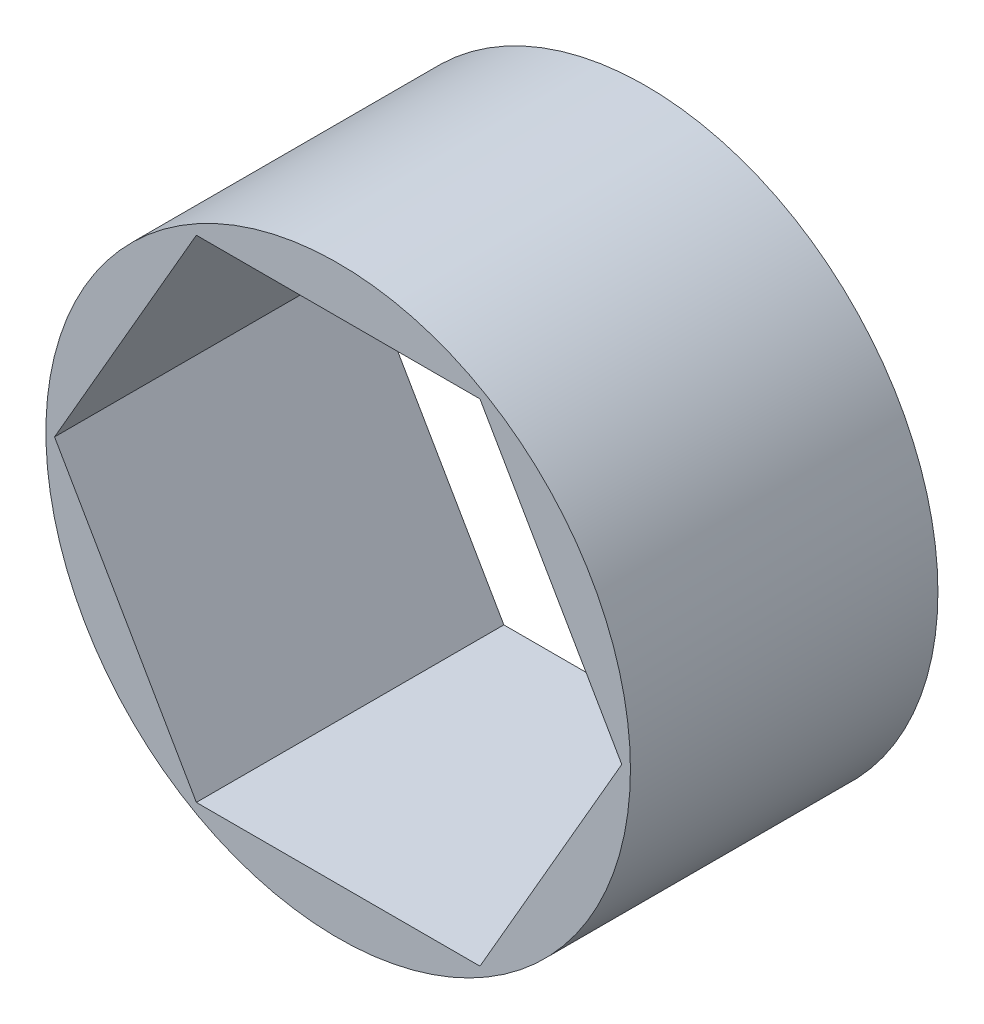
SolidWorks part; units mm, degrees
ref_plane "Front Plane" through (0, 0, 0) normal (0, 0, 1) x (1, 0, 0)
ref_plane "Top Plane" through (0, 0, 0) normal (0, 1, 0) x (1, 0, 0)
ref_plane "Right Plane" through (0, 0, 0) normal (1, 0, 0) x (0, 0, -1)
sketch "Sketch1" plane through (0, 0, 0) normal (0, 0, 1) x (1, 0, 0)
  circle A0 centre (0, 0) radius 7.5565
  dimension "D1" = 15.113
extrude "Boss-Extrude1" add sketch "Sketch1" along normal blind 7.9502
sketch "Sketch2" plane through (0, 0, 7.9502) normal (0, 0, 1) x (1, 0, 0)
  line L1 (7.3323, 0) -> (3.6662, 6.35)
  line L2 (3.6662, 6.35) -> (-3.6662, 6.35)
  line L3 (-3.6662, 6.35) -> (-7.3323, 0)
  line L4 (-7.3323, 0) -> (-3.6662, -6.35)
  line L5 (-3.6662, -6.35) -> (3.6662, -6.35)
  line L6 (3.6662, -6.35) -> (7.3323, 0)
  circle A0 centre (0, 0) radius 6.35 construction
  point P1 (0, -6.35)
  dimension "D1" = 12.7
extrude "Cut-Extrude1" cut sketch "Sketch2" against normal through all
